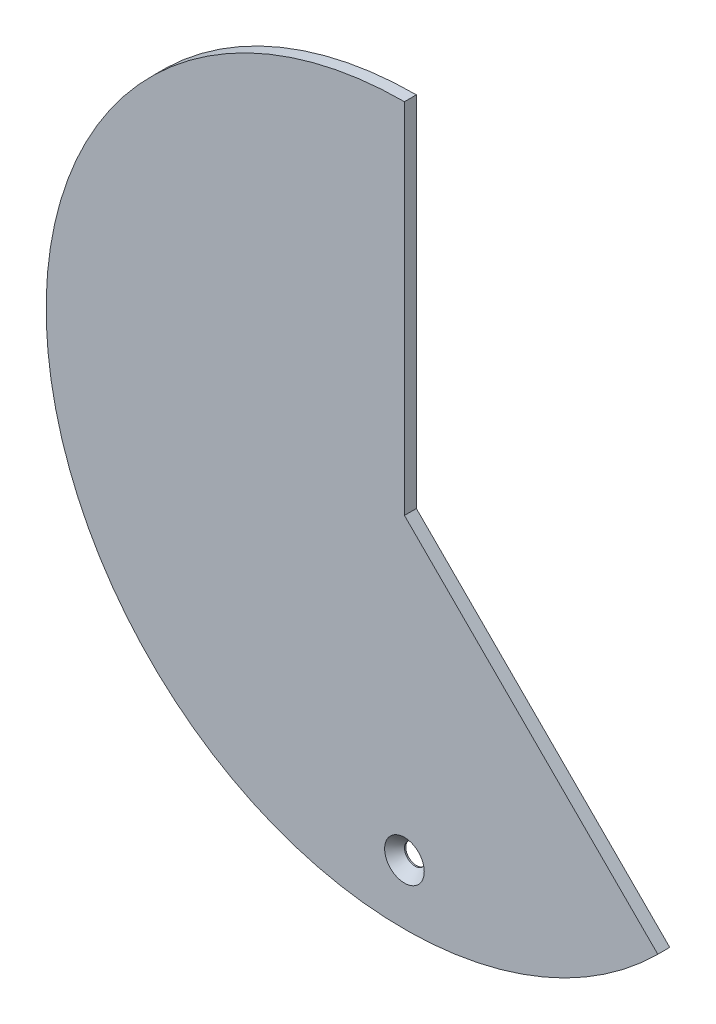
SolidWorks part; units mm, degrees
ref_plane "Front Plane" through (0, 0, 0) normal (0, 0, 1) x (1, 0, 0)
ref_plane "Top Plane" through (0, 0, 0) normal (0, 1, 0) x (1, 0, 0)
ref_plane "Right Plane" through (0, 0, 0) normal (1, 0, 0) x (0, 0, -1)
sketch "Sketch1" plane through (0, 0, 0) normal (0, 0, 1) x (1, 0, 0)
  line L0 (0, 0) -> (53.8815, -53.8815)
  line L1 (0, 0) -> (0, 76.2)
  arc A0 (0, 76.2) -> (53.8815, -53.8815) centre (0, 0) ccw
  dimension "D1" = 45
  dimension "D2" = 76.2
extrude "Boss-Extrude1" add sketch "Sketch1" along normal blind 2.54
hole_wizard "CSK for #8 Flat Head Machine Screw1" positions "Sketch2" profile "Sketch3" countersink size "#8" standard "ANSI Inch" end condition up to next
sketch "Sketch2" plane through (0, 0, 2.54) normal (0, 0, 1) x (1, 0, 0)
  line L0 (0, 0) -> (0, -63.5) construction
  point P0 (0, -63.5)
  dimension "D1" = 63.5
sketch "Sketch3" plane through (0, -63.5, 2.54) normal (1, 0, 0) x (0, -1, 0)
  line L0 (0, 0) -> (0, 2.54)
  line L1 (0, 2.54) -> (2.2479, 2.54)
  line L2 (2.2479, 2.54) -> (2.2479, 2.2645)
  line L3 (2.2479, 2.2645) -> (4.2164, 0)
  line L5 (4.2164, 0) -> (0, 0)
  line L6 (-2.2479, 2.2645) -> (-4.2164, 0) construction
  line L11 (0, -6.35) -> (0, 107.95) construction
  dimension "Thru Hole Dia." = 4.4958
  dimension "Thru Hole Depth" = 2.54
  dimension "Near C'Sink Dia." = 8.4328
  dimension "Near C'Sink Angle" = 82
